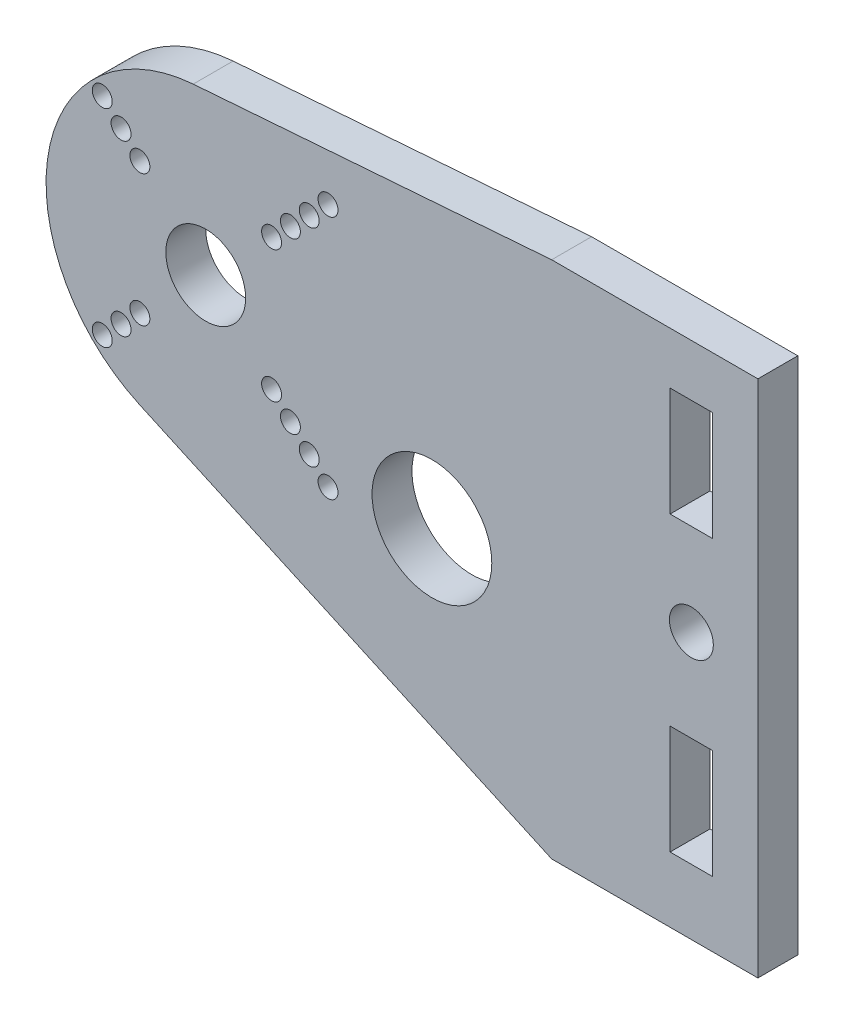
SolidWorks part; units mm, degrees
ref_plane "Спереди" through (0, 0, 0) normal (0, 0, 1) x (1, 0, 0)
ref_plane "Сверху" through (0, 0, 0) normal (0, 1, 0) x (1, 0, 0)
ref_plane "Справа" through (0, 0, 0) normal (1, 0, 0) x (0, 0, -1)
other "Configuration Table"
sketch "Eskiz_kontur" plane through (0, 0, 0) normal (0, 0, 1) x (1, 0, 0)
  line L0 (41.5, -25) -> (26, -25)
  line L1 (26, -25) -> (-4.9763, -10.9195)
  line L2 (41.5, 14) -> (41.5, -25)
  line L3 (26, 14) -> (41.5, 14)
  line L4 (-0.9415, 11.963) -> (26, 14)
  line L5 (38.1, -20.1) -> (38.1, -11.9)
  line L6 (38.1, -11.9) -> (34.9, -11.9)
  line L7 (34.9, -20.1) -> (38.1, -20.1)
  line L8 (34.9, -11.9) -> (34.9, -20.1)
  line L9 (38.1, 1.9) -> (38.1, 10.1)
  line L10 (38.1, 10.1) -> (34.9, 10.1)
  line L11 (34.9, 1.9) -> (38.1, 1.9)
  line L12 (34.9, 10.1) -> (34.9, 1.9)
  arc A0 (-4.9763, -10.9195) -> (-0.9415, 11.963) centre (0, 0) cw
extrude "Plastina" add sketch "Eskiz_kontur" along normal blind 3
sketch "Eskiz_otverstiya" plane through (0, 0, 0) normal (0, 0, 1) x (1, 0, 0)
  circle A0 centre (-7.7782, -7.7782) radius 0.75
  circle A1 centre (-6.364, -6.364) radius 0.75
  circle A2 centre (9.1924, -9.1924) radius 0.75
  circle A3 centre (7.7782, -7.7782) radius 0.75
  circle A4 centre (6.364, -6.364) radius 0.75
  circle A5 centre (17, -8) radius 4.5
  circle A6 centre (-4.9497, -4.9497) radius 0.75
  circle A7 centre (0, 0) radius 3
  circle A8 centre (4.9497, -4.9497) radius 0.75
  circle A9 centre (-4.9497, 4.9497) radius 0.75
  circle A10 centre (-6.364, 6.364) radius 0.75
  circle A11 centre (-7.7782, 7.7782) radius 0.75
  circle A12 centre (4.9497, 4.9497) radius 0.75
  circle A13 centre (6.364, 6.364) radius 0.75
  circle A14 centre (7.7782, 7.7782) radius 0.75
  circle A15 centre (9.1924, 9.1924) radius 0.75
  circle A16 centre (36.5, -5) radius 1.65
  dimension "d1" = 1.5
  dimension "d2" = 1.5
  dimension "d3" = 1.5
  dimension "d4" = 1.5
  dimension "d5" = 1.5
  dimension "d6" = 9
  dimension "d7" = 1.5
  dimension "d8" = 6
  dimension "d9" = 1.5
  dimension "d10" = 1.5
  dimension "d11" = 1.5
  dimension "d12" = 1.5
  dimension "d13" = 1.5
  dimension "d14" = 1.5
  dimension "d15" = 1.5
  dimension "d16" = 1.5
  dimension "d17" = 3.3
extrude "Otverstiya" cut sketch "Eskiz_otverstiya" against normal through all and the other way through all
equation "\"T3\" = 3"
equation "\"T5\" = 5"
equation "\"D_M3\" = 3.3"
equation "\"D_M2\" = 2.2"
equation "\"D_M3_TAP\" = 2.5"
equation "\"D_M4\" = 4.5"
equation "\"L1\" = 100"
equation "\"L2\" = 100"
equation "\"D1@Plastina\" = \"T3\""
equation "\"d17@Eskiz_otverstiya\" = \"D_M3\""
